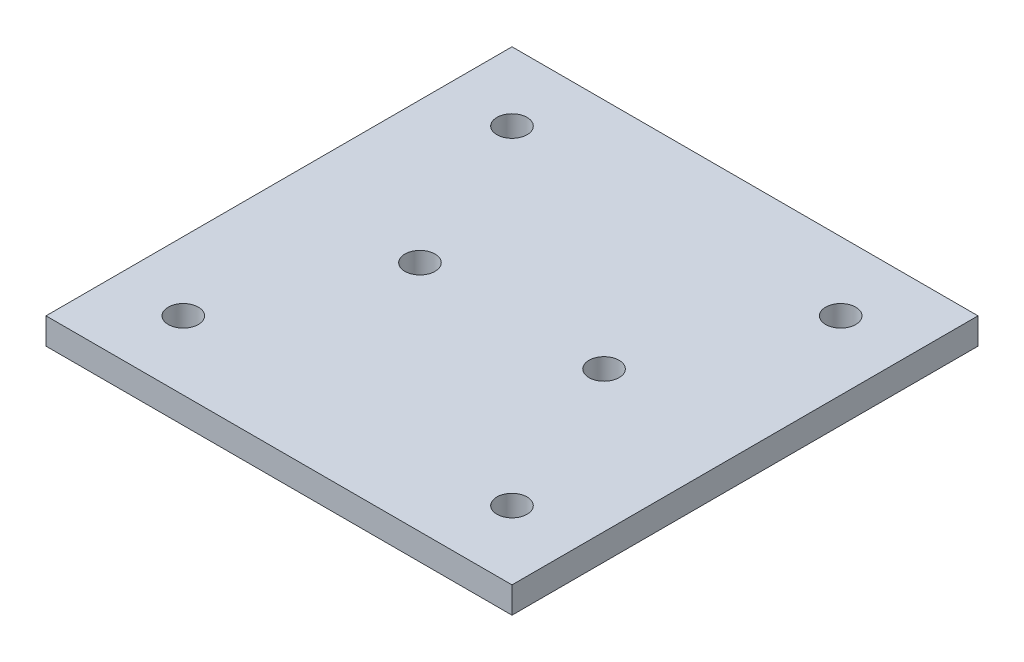
SolidWorks part; units mm, degrees
ref_plane "Front Plane" through (0, 0, 0) normal (0, 0, 1) x (1, 0, 0)
ref_plane "Top Plane" through (0, 0, 0) normal (0, 1, 0) x (1, 0, 0)
ref_plane "Right Plane" through (0, 0, 0) normal (1, 0, 0) x (0, 0, -1)
sketch "Sketch1" plane through (0, 0, 0) normal (0, 1, 0) x (1, 0, 0)
  line L0 (0, 17.7215) -> (0, -17.7215) construction
  line L1 (17.7215, -17.7215) -> (-17.7215, -17.7215)
  line L2 (17.7215, -17.7215) -> (17.7215, 17.7215)
  line L3 (17.7215, 17.7215) -> (-17.7215, 17.7215)
  line L4 (-17.7215, -17.7215) -> (-17.7215, 17.7215)
  line L5 (17.7215, -17.7215) -> (-17.7215, 17.7215) construction
  line L6 (17.7215, 17.7215) -> (-17.7215, -17.7215) construction
  line L7 (-17.7215, 0) -> (17.7215, 0) construction
  circle A0 centre (-12.5, 12.5) radius 1.1462
  circle A1 centre (12.5, 12.5) radius 1.1462
  circle A2 centre (12.5, -12.5) radius 1.1462
  circle A3 centre (-12.5, -12.5) radius 1.1462
  circle A4 centre (-7, 0) radius 1.1462
  circle A5 centre (7, 0) radius 1.1462
  point P0 (0, 0)
  dimension "D1" = 14
  dimension "D2" = 25
  dimension "D3" = 25
extrude "Boss-Extrude1" add sketch "Sketch1" along normal blind 2
